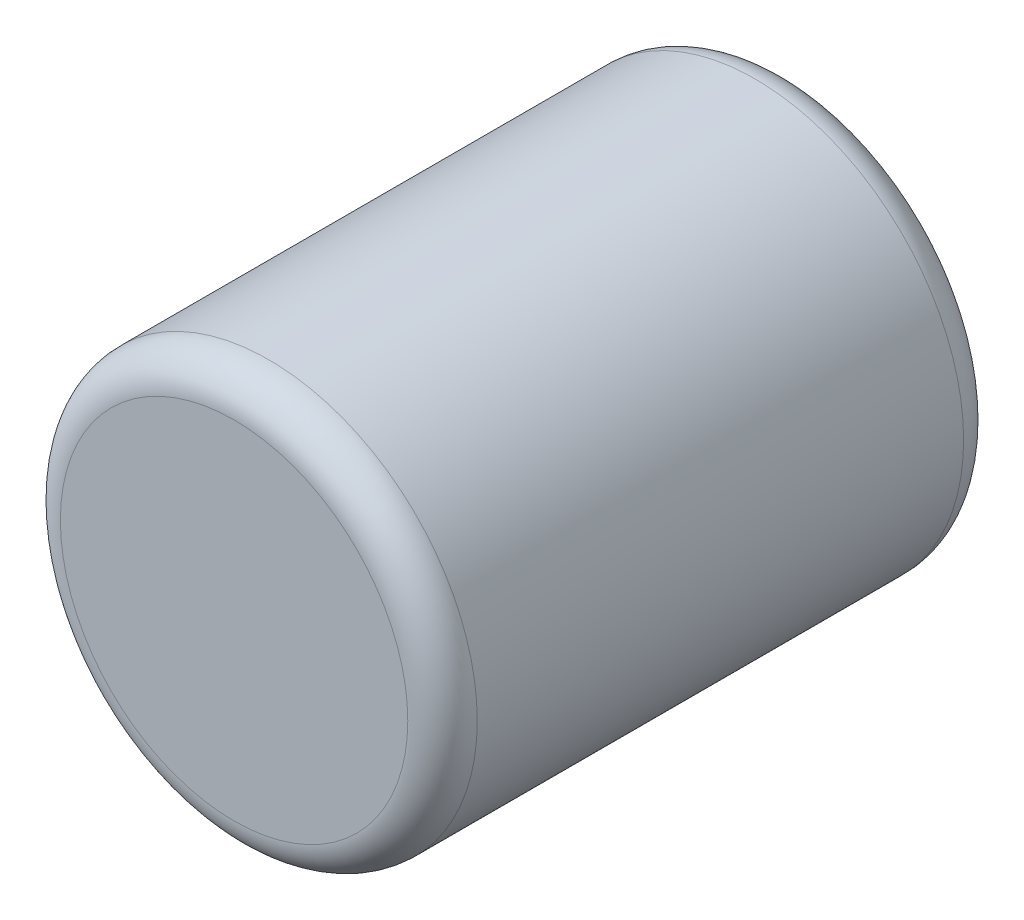
SolidWorks part; units mm, degrees
ref_plane "前基準面" through (0, 0, 0) normal (0, 0, 1) x (1, 0, 0)
ref_plane "上基準面" through (0, 0, 0) normal (0, 1, 0) x (1, 0, 0)
ref_plane "右基準面" through (0, 0, 0) normal (1, 0, 0) x (0, 0, -1)
sketch "草圖1" plane through (0, 0, 0) normal (0, 1, 0) x (1, 0, 0)
  line L0 (2.5, 0) -> (0, 0)
  line L1 (0, 0) -> (0, -8)
  line L2 (0, -8) -> (2.5, -8)
  line L3 (3, -7.5) -> (3, -0.5)
  line L4 (0, 0.0027) -> (0, -8.0027) construction
  arc A0 (2.5, -8) -> (3, -7.5) centre (2.5, -7.5) ccw
  arc A1 (3, -0.5) -> (2.5, 0) centre (2.5, -0.5) ccw
revolve "旋轉1" add sketch "草圖1" angle 360 about L4
